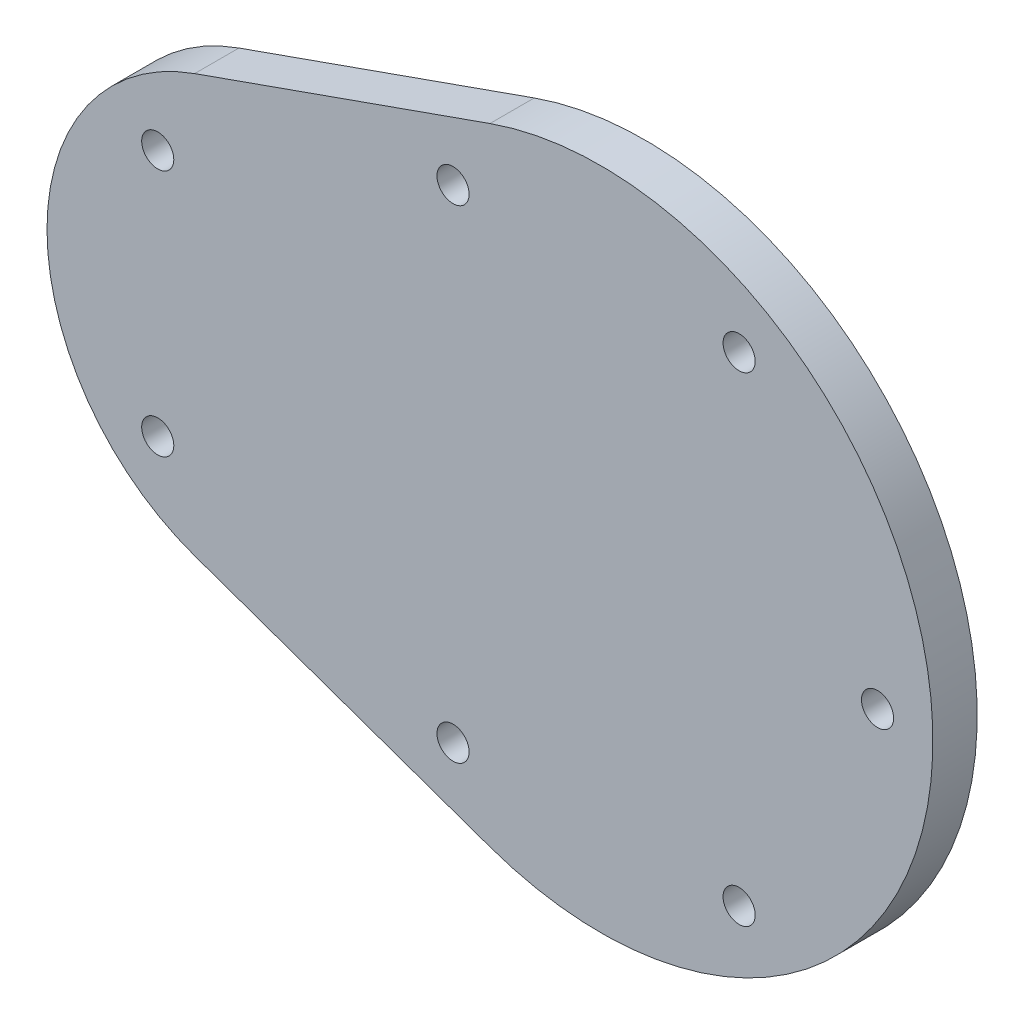
SolidWorks part; units mm, degrees
material "Pin"
ref_plane "Plan de face" through (0, 0, 0) normal (0, 0, 1) x (1, 0, 0)
ref_plane "Plan de dessus" through (0, 0, 0) normal (0, 1, 0) x (1, 0, 0)
ref_plane "Plan de droite" through (0, 0, 0) normal (1, 0, 0) x (0, 0, -1)
sketch "Esquisse1" plane through (0, 0, 0) normal (0, 0, 1) x (1, 0, 0)
  line L8 (-20, 56.5685) -> (-73.3333, 37.7124)
  line L9 (-73.3333, -37.7124) -> (-20, -56.5685)
  arc A2 (-73.3333, -37.7124) -> (-73.3333, 37.7124) centre (-60, 0) cw
  arc A3 (-20, 56.5685) -> (60, 0) centre (0, 0) cw
  arc A4 (-20, -56.5685) -> (60, 0) centre (0, 0) ccw
  point P5 (-100, 0)
  dimension "D1" = 40
  dimension "D3" = 60
  dimension "D2" = 60
extrude "Boss.-Extru.1" add sketch "Esquisse1" along normal blind 8 contours A4 L9 A2 L8 A3
hole_wizard "Dégagement M52" positions "Esquisse4" profile "Esquisse5" hole size "M5" standard "ISO"
sketch "Esquisse4" plane through (15, 0, 8) normal (0, 0, 1) x (0, 1, 0)
  line L0 (0, 115) -> (0, -45) construction
  line L10 (47.1405, 31.6667) -> (28.2843, 85)
  line L11 (-28.2843, 85) -> (-47.1405, 31.6667)
  arc A10 (-47.1405, 31.6667) -> (47.1405, 31.6667) centre (0, 15) ccw
  arc A11 (28.2843, 85) -> (-28.2843, 85) centre (0, 75) ccw
  point P61 (0, -35)
  point P63 (-43.3013, -10)
  point P65 (43.3013, -10)
  point P69 (-22.3607, 95)
  point P71 (22.3607, 95)
  point P76 (-43.6049, 41.6667)
  point P78 (43.6049, 41.6667)
sketch "Esquisse5" plane through (-26.6667, 43.6049, 8) normal (1, 0, 0) x (0, -1, 0)
  line L0 (0, 0) -> (0, 91.7425)
  line L1 (0, 91.7425) -> (2.9, 90)
  line L2 (2.9, 90) -> (2.9, 0)
  line L3 (2.9, 0) -> (0, 0)
  line L4 (0, 91.7425) -> (-2.9, 90) construction
  line L5 (0, -6.35) -> (0, 107.95) construction
  dimension "Diamètre du perçage" = 5.8
  dimension "Profondeur du perçage" = 90
  dimension "Angle de pointe" = 118
